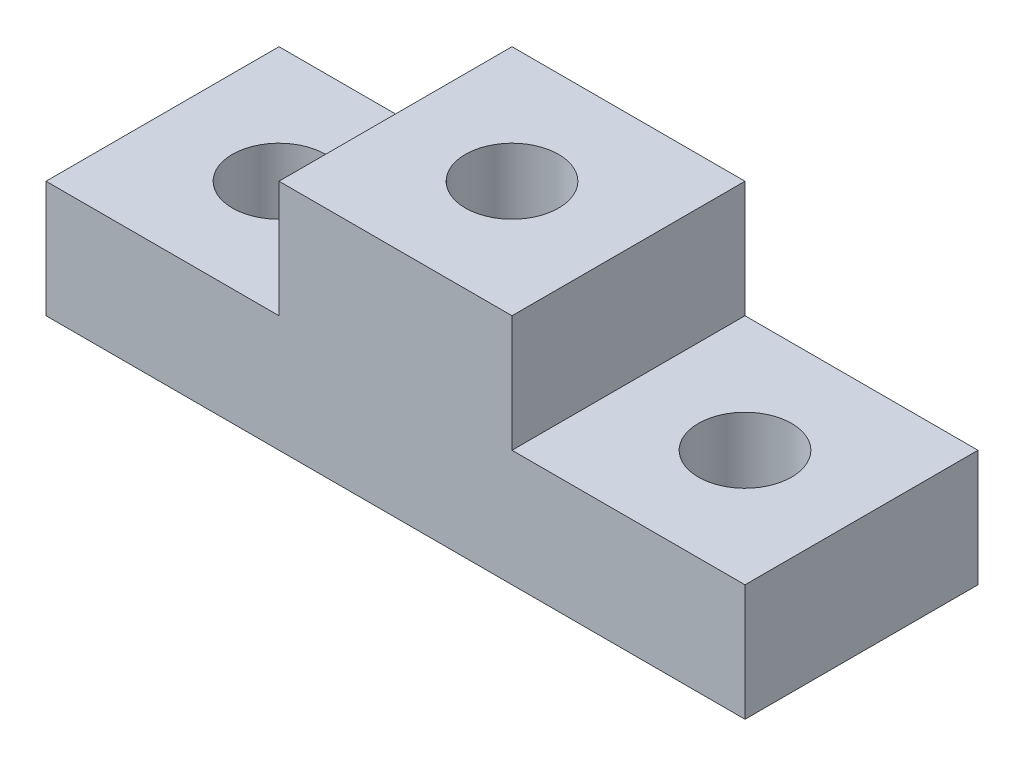
SolidWorks part; units mm, degrees
ref_plane "Front Plane" through (0, 0, 0) normal (0, 0, 1) x (1, 0, 0)
ref_plane "Top Plane" through (0, 0, 0) normal (0, 1, 0) x (1, 0, 0)
ref_plane "Right Plane" through (0, 0, 0) normal (1, 0, 0) x (0, 0, -1)
sketch "Sketch1" plane through (0, 0, 0) normal (0, 0, 1) x (1, 0, 0)
  line L0 (15, 0) -> (15, 12.6753) construction
  line L1 (10, 0) -> (20, 0)
  line L2 (0, -5) -> (0, -10)
  line L3 (0, -10) -> (30, -10)
  line L4 (30, -5) -> (30, -10)
  line L5 (0, -5) -> (10, -5)
  line L6 (10, -5) -> (10, 0)
  line L7 (20, -5) -> (20, 0)
  line L8 (30, -5) -> (20, -5)
extrude "Boss-Extrude1" add sketch "Sketch1" along normal blind 10
sketch "Sketch2" plane through (0, 0, 0) normal (0, 1, 0) x (1, 0, 0)
  circle A0 centre (15, -5) radius 2
extrude "Cut-Extrude1" cut sketch "Sketch2" against normal through all
cosmetic thread "Cosmetic Thread1" parameters "D2"=4
sketch "Sketch3" plane through (0, -5, 0) normal (0, 1, 0) x (1, 0, 0)
  circle A0 centre (5, -5) radius 2
  circle A1 centre (25, -5) radius 2
extrude "Cut-Extrude2" cut sketch "Sketch3" against normal through all
